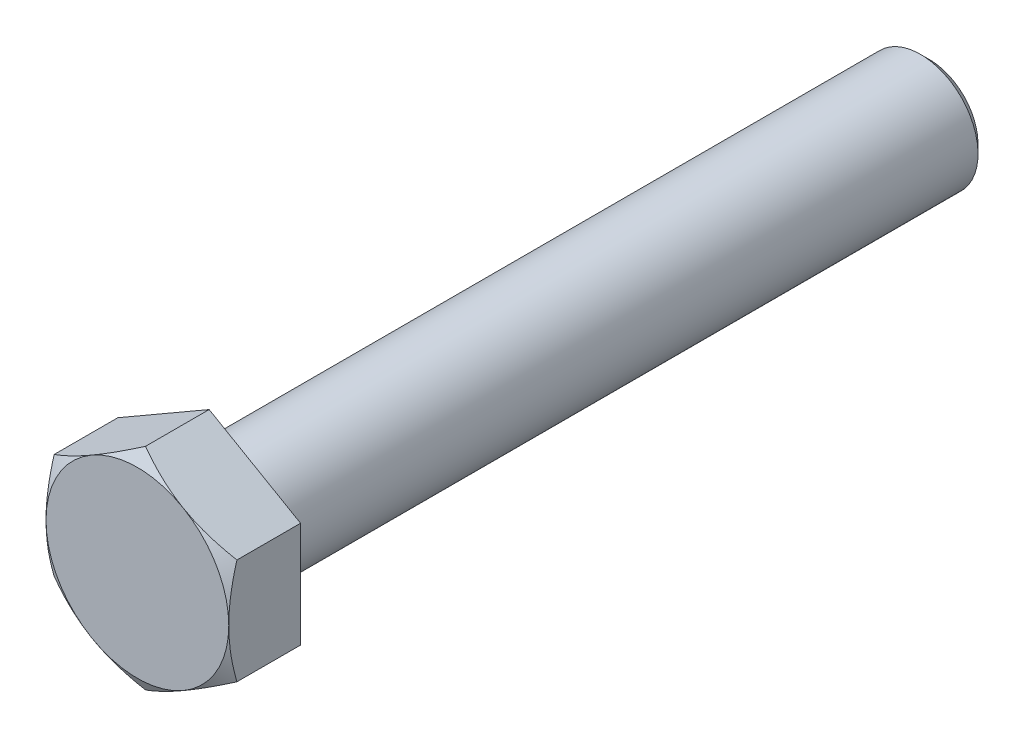
SolidWorks part; units mm, degrees
ref_plane "Front Plane" through (0, 0, 0) normal (0, 0, 1) x (1, 0, 0)
ref_plane "Top Plane" through (0, 0, 0) normal (0, 1, 0) x (1, 0, 0)
ref_plane "Right Plane" through (0, 0, 0) normal (1, 0, 0) x (0, 0, -1)
sketch "Sketch1" plane through (0, 0, 0) normal (0, 0, 1) x (1, 0, 0)
  line L0 (0, 0) -> (0, 7.3497) construction
  line L2 (0, 7.3497) -> (-6.365, 3.6748)
  line L3 (-6.365, 3.6748) -> (-6.365, -3.6748)
  line L4 (-6.365, -3.6748) -> (0, -7.3497)
  line L5 (0, -7.3497) -> (6.365, -3.6748)
  line L6 (6.365, -3.6748) -> (6.365, 3.6748)
  line L7 (6.365, 3.6748) -> (0, 7.3497)
  circle A0 centre (0, 0) radius 6.365 construction
  dimension "HEX" = 12.73
extrude "Boss-Extrude1" add sketch "Sketch1" along normal blind 5.15
sketch "Sketch2" plane through (0, 0, 0) normal (1, 0, 0) x (0, 0, -1)
  line L0 (0, 0) -> (50, 0) construction
  line L1 (0, 0) -> (0, 4.6)
  line L4 (49.4, 4) -> (50, 3.4)
  line L7 (50, 3.4) -> (50, 0)
  line L8 (50, 0) -> (0, 0)
  line L9 (49.4, 4) -> (0.6, 4)
  arc A3 (0.6, 4) -> (0, 4.6) centre (0.6, 4.6) cw
  dimension "LENGTH" = 50
  dimension "WIDTH2" = 6.8
  dimension "WIDTH1" = 8
  dimension "D5" = 45
  dimension "DA" = 9.2
revolve "Revolve1" add sketch "Sketch2" angle 360 about L0
cosmetic thread "Cosmetic Thread1" parameters "D1"=46.25, "D2"=8
sketch "Sketch3" plane through (0, 0, 0) normal (1, 0, 0) x (0, 0, -1)
  line L0 (-12.2049, 0) -> (129.7862, 0) construction
  line L1 (-5.15, 7.3497) -> (-4.5815, 7.3497)
  line L2 (-0.15, 7.3497) -> (-0.15, 5.8866)
  line L3 (-4.5815, 7.3497) -> (-5.15, 6.365)
  line L4 (-0.15, 5.8866) -> (0, 5.8)
  line L5 (-5.15, 6.365) -> (-5.15, 7.3497)
  line L6 (0, -3.6748) -> (0, 3.6748) construction
  line L7 (-5.15, 7.3497) -> (0, 7.3497) construction
  line L8 (-5.15, 3.6748) -> (-5.15, 7.3497) construction
  line L10 (0, 5.8) -> (0, 7.3497)
  line L11 (0, 7.3497) -> (-0.15, 7.3497)
  dimension "D1" = 30
  dimension "SAME AS HEX" = 12.73
  dimension "D3" = 30
  dimension "C" = 0.15
  dimension "DW" = 11.6
revolve "Cut-Revolve1" cut sketch "Sketch3" angle 360 about L0
